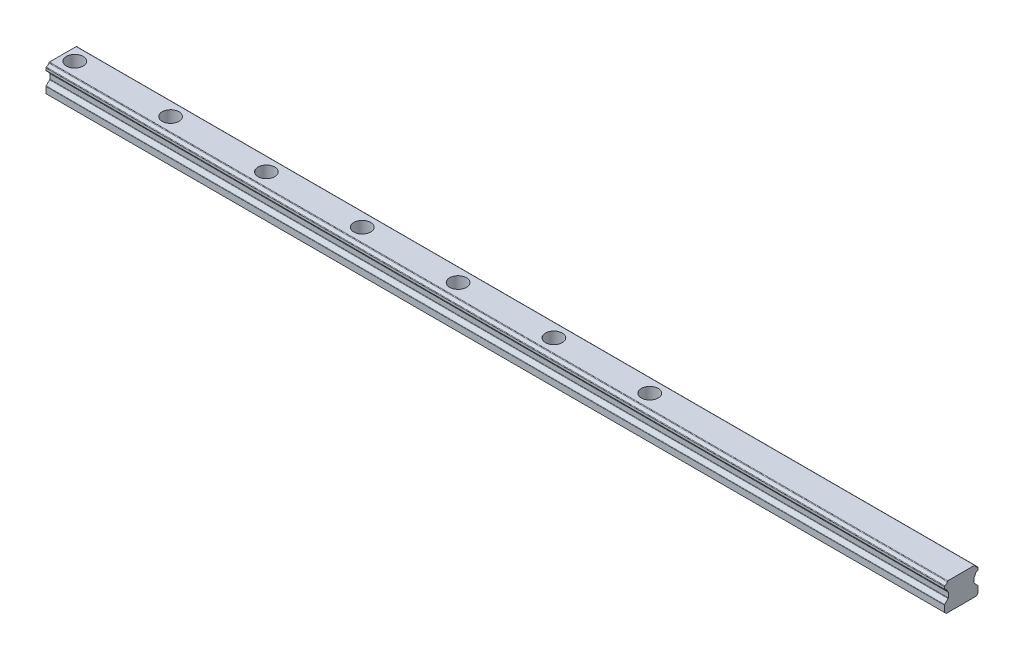
SolidWorks part; units mm, degrees
ref_plane "Front Plane" through (0, 0, 0) normal (0, 0, 1) x (1, 0, 0)
ref_plane "Top Plane" through (0, 0, 0) normal (0, 1, 0) x (1, 0, 0)
ref_plane "Right Plane" through (0, 0, 0) normal (1, 0, 0) x (0, 0, -1)
ref_plane "Plane1" through (-10, 0, 0) normal (1, 0, 0) x (0, 0, -1)
sketch "Sketch1" plane through (-10, 0, 0) normal (1, 0, 0) x (0, 0, -1)
  line L0 (-14, 20.1484) -> (-14, 18.3516)
  line L1 (-11.4582, 15.3602) -> (-11.005, 14.907)
  line L2 (-10.8, 14.4121) -> (-10.8, 10.4908)
  line L3 (-11.0056, 9.9944) -> (-13.7956, 7.2044)
  line L4 (-14, 6.7109) -> (-14, 1.5)
  line L5 (-14, 1.5) -> (-12.5, 0)
  line L6 (-12.5, 0) -> (12.5, 0)
  line L7 (12.5, 0) -> (14, 1.5)
  line L8 (14, 1.5) -> (14, 6.7109)
  line L9 (13.7956, 7.2044) -> (11.0056, 9.9944)
  line L10 (10.8, 10.4908) -> (10.8, 14.4121)
  line L11 (11.005, 14.907) -> (11.4582, 15.3602)
  line L12 (14, 18.3516) -> (14, 20.1484)
  line L13 (11.147, 23) -> (-11.147, 23)
  arc A0 (-13.5924, 20.6398) -> (-14, 20.1484) centre (-13.5072, 20.1544) ccw
  arc A1 (-14, 18.3516) -> (-13.5924, 17.8602) centre (-13.5025, 18.3495) ccw
  arc A2 (-13.5924, 17.8602) -> (-11.6026, 15.669) centre (-14.042, 15.4529) cw
  arc A3 (-11.6026, 15.669) -> (-11.4582, 15.3602) centre (-11.1281, 15.7028) ccw
  arc A4 (-11.005, 14.907) -> (-10.8, 14.4121) centre (-11.4843, 14.4185) cw
  arc A5 (-10.8, 10.4908) -> (-11.0056, 9.9944) centre (-11.5021, 10.4908) cw
  arc A6 (-13.7956, 7.2044) -> (-14, 6.7109) centre (-13.302, 6.7109) ccw
  arc A7 (14, 6.7109) -> (13.7956, 7.2044) centre (13.302, 6.7109) ccw
  arc A8 (11.0056, 9.9944) -> (10.8, 10.4908) centre (11.5021, 10.4908) cw
  arc A9 (10.8, 14.4121) -> (11.005, 14.907) centre (11.4843, 14.4185) cw
  arc A10 (11.4582, 15.3602) -> (11.6026, 15.669) centre (11.1281, 15.7028) ccw
  arc A11 (11.6026, 15.669) -> (13.5924, 17.8602) centre (14.042, 15.4529) cw
  arc A12 (13.5924, 17.8602) -> (14, 18.3516) centre (13.5025, 18.3495) ccw
  arc A13 (14, 20.1484) -> (13.5924, 20.6398) centre (13.5072, 20.1544) ccw
  arc A14 (13.5924, 20.6398) -> (11.6358, 22.5932) centre (14.0457, 23.0505) cw
  arc A15 (11.6358, 22.5932) -> (11.147, 23) centre (11.1545, 22.512) ccw
  arc A16 (-11.147, 23) -> (-11.6358, 22.5932) centre (-11.1545, 22.512) ccw
  arc A17 (-11.6358, 22.5932) -> (-13.5924, 20.6398) centre (-14.0457, 23.0505) cw
extrude "Boss-Extrude1" add sketch "Sketch1" along normal blind 750
ref_plane "Plane2" through (0, 0, 0) normal (0, 0, 1) x (1, 0, 0)
sketch "Sketch2" plane through (0, 0, 0) normal (0, 0, 1) x (1, 0, 0)
  line L0 (0, 23) -> (7, 23)
  line L1 (7, 23) -> (7, 11)
  line L2 (7, 11) -> (4.5, 11)
  line L3 (4.5, 11) -> (4.5, 0)
  line L4 (4.5, 0) -> (0, 0)
  line L5 (0, 0) -> (0, 23)
  line L6 (0, 0) -> (0, 23) construction
revolve "Cut-Revolve1" cut sketch "Sketch2" angle 360 about L6
ref_plane "Plane3" through (0, 0, 0) normal (0, 0, 1) x (1, 0, 0)
sketch "Sketch3" plane through (0, 0, 0) normal (0, 0, 1) x (1, 0, 0)
  line L0 (80, 23) -> (87, 23)
  line L1 (87, 23) -> (87, 11)
  line L2 (87, 11) -> (84.5, 11)
  line L3 (84.5, 11) -> (84.5, 0)
  line L4 (84.5, 0) -> (80, 0)
  line L5 (80, 0) -> (80, 23)
  line L6 (80, 0) -> (80, 23) construction
revolve "Cut-Revolve2" cut sketch "Sketch3" angle 360 about L6
ref_plane "Plane4" through (0, 0, 0) normal (0, 0, 1) x (1, 0, 0)
sketch "Sketch4" plane through (0, 0, 0) normal (0, 0, 1) x (1, 0, 0)
  line L0 (160, 23) -> (167, 23)
  line L1 (167, 23) -> (167, 11)
  line L2 (167, 11) -> (164.5, 11)
  line L3 (164.5, 11) -> (164.5, 0)
  line L4 (164.5, 0) -> (160, 0)
  line L5 (160, 0) -> (160, 23)
  line L6 (160, 0) -> (160, 23) construction
revolve "Cut-Revolve3" cut sketch "Sketch4" angle 360 about L6
ref_plane "Plane5" through (0, 0, 0) normal (0, 0, 1) x (1, 0, 0)
sketch "Sketch5" plane through (0, 0, 0) normal (0, 0, 1) x (1, 0, 0)
  line L0 (240, 23) -> (247, 23)
  line L1 (247, 23) -> (247, 11)
  line L2 (247, 11) -> (244.5, 11)
  line L3 (244.5, 11) -> (244.5, 0)
  line L4 (244.5, 0) -> (240, 0)
  line L5 (240, 0) -> (240, 23)
  line L6 (240, 0) -> (240, 23) construction
revolve "Cut-Revolve4" cut sketch "Sketch5" angle 360 about L6
ref_plane "Plane6" through (0, 0, 0) normal (0, 0, 1) x (1, 0, 0)
sketch "Sketch6" plane through (0, 0, 0) normal (0, 0, 1) x (1, 0, 0)
  line L0 (320, 23) -> (327, 23)
  line L1 (327, 23) -> (327, 11)
  line L2 (327, 11) -> (324.5, 11)
  line L3 (324.5, 11) -> (324.5, 0)
  line L4 (324.5, 0) -> (320, 0)
  line L5 (320, 0) -> (320, 23)
  line L6 (320, 0) -> (320, 23) construction
revolve "Cut-Revolve5" cut sketch "Sketch6" angle 360 about L6
ref_plane "Plane7" through (0, 0, 0) normal (0, 0, 1) x (1, 0, 0)
sketch "Sketch7" plane through (0, 0, 0) normal (0, 0, 1) x (1, 0, 0)
  line L0 (400, 23) -> (407, 23)
  line L1 (407, 23) -> (407, 11)
  line L2 (407, 11) -> (404.5, 11)
  line L3 (404.5, 11) -> (404.5, 0)
  line L4 (404.5, 0) -> (400, 0)
  line L5 (400, 0) -> (400, 23)
  line L6 (400, 0) -> (400, 23) construction
revolve "Cut-Revolve6" cut sketch "Sketch7" angle 360 about L6
ref_plane "Plane8" through (0, 0, 0) normal (0, 0, 1) x (1, 0, 0)
sketch "Sketch8" plane through (0, 0, 0) normal (0, 0, 1) x (1, 0, 0)
  line L0 (480, 23) -> (487, 23)
  line L1 (487, 23) -> (487, 11)
  line L2 (487, 11) -> (484.5, 11)
  line L3 (484.5, 11) -> (484.5, 0)
  line L4 (484.5, 0) -> (480, 0)
  line L5 (480, 0) -> (480, 23)
  line L6 (480, 0) -> (480, 23) construction
revolve "Cut-Revolve7" cut sketch "Sketch8" angle 360 about L6
